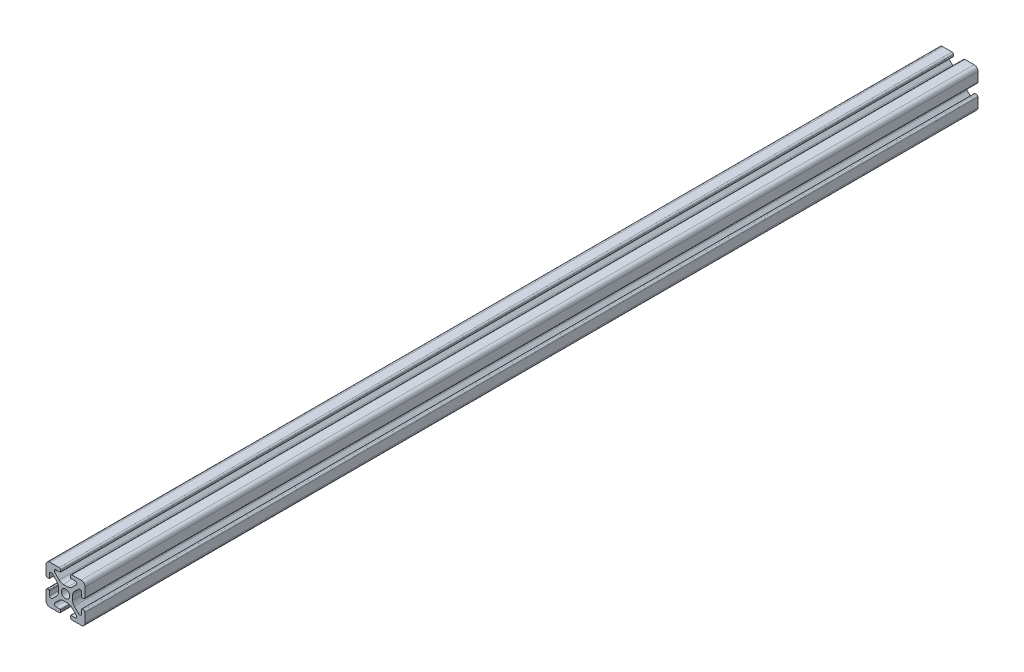
SolidWorks part; units mm, degrees
ref_plane "Front Plane" through (0, 0, 0) normal (0, 0, 1) x (1, 0, 0)
ref_plane "Top Plane" through (0, 0, 0) normal (0, 1, 0) x (1, 0, 0)
ref_plane "Right Plane" through (0, 0, 0) normal (1, 0, 0) x (0, 0, -1)
sketch "Sketch1" plane through (0, 0, 0) normal (0, 0, 1) x (1, 0, 0)
  line L2 (-9.9949, 7.9883) -> (-9.9949, 3.2893)
  line L3 (-7.9883, 9.9949) -> (-3.2893, 9.9949)
  line L4 (-2.5019, 9.2075) -> (-2.5019, 8.4963)
  line L5 (-2.8067, 8.1915) -> (-4.9149, 8.1915)
  line L6 (-5.5076, 6.7606) -> (-3.2528, 4.5058)
  line L7 (-6.7606, 5.5076) -> (-4.5058, 3.2528)
  line L8 (-8.1915, 4.9149) -> (-8.1915, 2.8067)
  line L9 (-8.4963, 2.5019) -> (-9.2075, 2.5019)
  line L11 (-1.1334, 3.6279) -> (1.1334, 3.6279)
  line L12 (-3.6279, 1.1334) -> (-3.6279, -1.1334)
  line L13 (8.4963, 2.5019) -> (9.2075, 2.5019)
  line L14 (8.1915, 4.9149) -> (8.1915, 2.8067)
  line L15 (9.9949, 7.9883) -> (9.9949, 3.2893)
  line L16 (7.9883, 9.9949) -> (3.2893, 9.9949)
  line L17 (2.5019, 9.2075) -> (2.5019, 8.4963)
  line L18 (2.8067, 8.1915) -> (4.9149, 8.1915)
  line L19 (3.6279, 1.1334) -> (3.6279, -1.1334)
  line L20 (5.5076, 6.7606) -> (3.2528, 4.5058)
  line L21 (6.7606, 5.5076) -> (4.5058, 3.2528)
  line L22 (-8.4963, -2.5019) -> (-9.2075, -2.5019)
  line L23 (-8.1915, -4.9149) -> (-8.1915, -2.8067)
  line L24 (-6.7606, -5.5076) -> (-4.5058, -3.2528)
  line L25 (-5.5076, -6.7606) -> (-3.2528, -4.5058)
  line L26 (-2.8067, -8.1915) -> (-4.9149, -8.1915)
  line L27 (-2.5019, -9.2075) -> (-2.5019, -8.4963)
  line L28 (-7.9883, -9.9949) -> (-3.2893, -9.9949)
  line L29 (-9.9949, -7.9883) -> (-9.9949, -3.2893)
  line L30 (9.9949, -7.9883) -> (9.9949, -3.2893)
  line L31 (7.9883, -9.9949) -> (3.2893, -9.9949)
  line L32 (2.5019, -9.2075) -> (2.5019, -8.4963)
  line L33 (2.8067, -8.1915) -> (4.9149, -8.1915)
  line L34 (5.5076, -6.7606) -> (3.2528, -4.5058)
  line L35 (6.7606, -5.5076) -> (4.5058, -3.2528)
  line L36 (8.1915, -4.9149) -> (8.1915, -2.8067)
  line L37 (8.4963, -2.5019) -> (9.2075, -2.5019)
  line L38 (-1.1334, -3.6279) -> (1.1334, -3.6279)
  circle A0 centre (0, 0) radius 2.1463
  arc A1 (-9.9949, 7.9883) -> (-7.9883, 9.9949) centre (-7.9883, 7.9883) cw
  arc A2 (-6.7606, 5.5076) -> (-8.1915, 4.9149) centre (-7.3533, 4.9149) ccw
  arc A3 (-4.9149, 8.1915) -> (-5.5076, 6.7606) centre (-4.9149, 7.3533) ccw
  arc A4 (-3.2893, 9.9949) -> (-2.5019, 9.2075) centre (-3.2893, 9.2075) cw
  arc A5 (-9.9949, 3.2893) -> (-9.2075, 2.5019) centre (-9.2075, 3.2893) ccw
  arc A6 (-8.1915, 2.8067) -> (-8.4963, 2.5019) centre (-8.4963, 2.8067) cw
  arc A7 (-2.5019, 8.4963) -> (-2.8067, 8.1915) centre (-2.8067, 8.4963) cw
  arc A8 (-1.1334, 3.6279) -> (-3.2528, 4.5058) centre (-1.1334, 6.6251) cw
  arc A9 (-3.6279, 1.1334) -> (-4.5058, 3.2528) centre (-6.6251, 1.1334) ccw
  arc A10 (8.1915, 2.8067) -> (8.4963, 2.5019) centre (8.4963, 2.8067) ccw
  arc A11 (9.9949, 3.2893) -> (9.2075, 2.5019) centre (9.2075, 3.2893) cw
  arc A12 (9.9949, 7.9883) -> (7.9883, 9.9949) centre (7.9883, 7.9883) ccw
  arc A13 (3.2893, 9.9949) -> (2.5019, 9.2075) centre (3.2893, 9.2075) ccw
  arc A14 (2.5019, 8.4963) -> (2.8067, 8.1915) centre (2.8067, 8.4963) ccw
  arc A15 (1.1334, 3.6279) -> (3.2528, 4.5058) centre (1.1334, 6.6251) ccw
  arc A16 (3.6279, 1.1334) -> (4.5058, 3.2528) centre (6.6251, 1.1334) cw
  arc A17 (6.7606, 5.5076) -> (8.1915, 4.9149) centre (7.3533, 4.9149) cw
  arc A18 (4.9149, 8.1915) -> (5.5076, 6.7606) centre (4.9149, 7.3533) cw
  arc A19 (-3.6279, -1.1334) -> (-4.5058, -3.2528) centre (-6.6251, -1.1334) cw
  arc A20 (-1.1334, -3.6279) -> (-3.2528, -4.5058) centre (-1.1334, -6.6251) ccw
  arc A21 (-2.5019, -8.4963) -> (-2.8067, -8.1915) centre (-2.8067, -8.4963) ccw
  arc A22 (-8.1915, -2.8067) -> (-8.4963, -2.5019) centre (-8.4963, -2.8067) ccw
  arc A23 (-9.9949, -3.2893) -> (-9.2075, -2.5019) centre (-9.2075, -3.2893) cw
  arc A24 (-3.2893, -9.9949) -> (-2.5019, -9.2075) centre (-3.2893, -9.2075) ccw
  arc A25 (-4.9149, -8.1915) -> (-5.5076, -6.7606) centre (-4.9149, -7.3533) cw
  arc A26 (-6.7606, -5.5076) -> (-8.1915, -4.9149) centre (-7.3533, -4.9149) cw
  arc A27 (-9.9949, -7.9883) -> (-7.9883, -9.9949) centre (-7.9883, -7.9883) ccw
  arc A28 (9.9949, -7.9883) -> (7.9883, -9.9949) centre (7.9883, -7.9883) cw
  arc A29 (6.7606, -5.5076) -> (8.1915, -4.9149) centre (7.3533, -4.9149) ccw
  arc A30 (4.9149, -8.1915) -> (5.5076, -6.7606) centre (4.9149, -7.3533) ccw
  arc A31 (3.2893, -9.9949) -> (2.5019, -9.2075) centre (3.2893, -9.2075) cw
  arc A32 (9.9949, -3.2893) -> (9.2075, -2.5019) centre (9.2075, -3.2893) ccw
  arc A33 (8.1915, -2.8067) -> (8.4963, -2.5019) centre (8.4963, -2.8067) cw
  arc A34 (2.5019, -8.4963) -> (2.8067, -8.1915) centre (2.8067, -8.4963) cw
  arc A35 (1.1334, -3.6279) -> (3.2528, -4.5058) centre (1.1334, -6.6251) cw
  arc A36 (3.6279, -1.1334) -> (4.5058, -3.2528) centre (6.6251, -1.1334) ccw
extrude "Boss-Extrude1" add sketch "Sketch1" along normal mid plane 457.2
